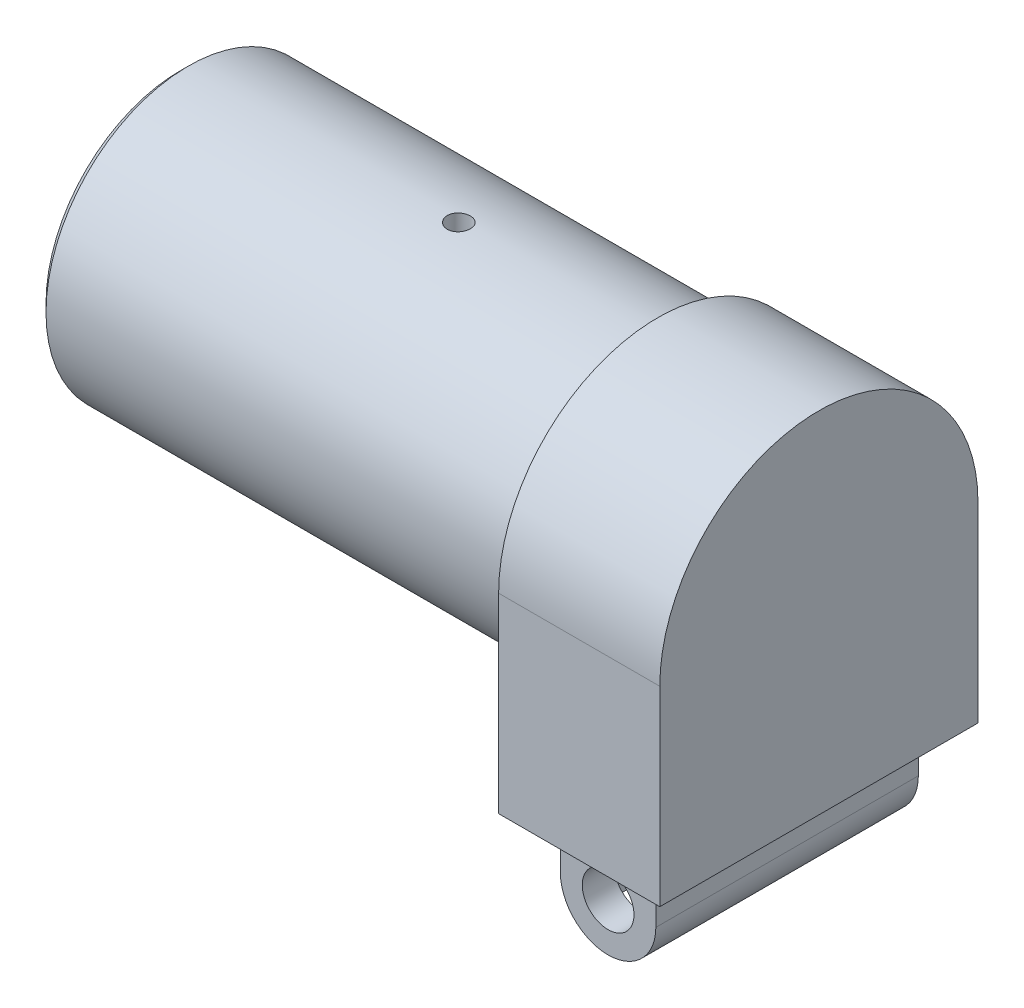
SolidWorks part; units mm, degrees
ref_plane "정면" through (0, 0, 0) normal (0, 0, 1) x (1, 0, 0)
ref_plane "윗면" through (0, 0, 0) normal (0, 1, 0) x (1, 0, 0)
ref_plane "우측면" through (0, 0, 0) normal (1, 0, 0) x (0, 0, -1)
sketch "스케치1" plane through (0, 0, 0) normal (1, 0, 0) x (0, 0, -1)
  line L0 (-20, 0) -> (-20, -24)
  line L1 (-20, -24) -> (20, -24)
  line L2 (20, -24) -> (20, 0)
  circle A0 centre (0, 0) radius 20
  dimension "D1" = 40
  dimension "D2" = 24
extrude "보스-돌출1" add sketch "스케치1" along normal blind 10 and the other way blind 10.26 contours A0 L0 L1 | A0 L1 L2 | A0
sketch "스케치4" plane through (-10.26, 0, 0) normal (-1, 0, 0) x (0, 0, 1)
  circle A0 centre (0, 0) radius 17.9
  dimension "D1" = 35.8
extrude "보스-돌출3" add sketch "스케치4" along normal blind 60
sketch "스케치15" plane through (0, 0, 0) normal (0, 0, 1) x (1, 0, 0)
  line L0 (-6, -30) -> (-6, -24)
  line L1 (-6, -24) -> (6, -24)
  line L2 (6, -24) -> (6, -30)
  line L3 (-10.26, -24) -> (10, -24) construction
  circle A0 centre (0, -30) radius 6
  point P9 (0, 0)
  dimension "D2" = 12
  dimension "D1" = 30
extrude "보스-돌출7" add sketch "스케치15" along normal blind 16.5 and the other way blind 16.5 contours A0 L1 L0 | A0 | A0 L2 L1
sketch "스케치17" plane through (0, 0, -16.5) normal (0, 0, -1) x (-1, 0, 0)
  circle A0 centre (0, -30) radius 3.25
  dimension "D1" = 6.5
extrude "컷-돌출3" cut sketch "스케치17" against normal blind 13
mirror "대칭 복사7" about plane through (0, 0, 0) normal (0, 0, 1) of "컷-돌출3"
ref_plane "평면2" through (0, 0, -10.5) normal (0, 0, -1) x (-1, 0, 0)
sketch "스케치18" plane through (0, 0, -10.5) normal (0, 0, -1) x (-1, 0, 0)
  line L0 (-4.2, -32.4249) -> (-4.2, -36)
  line L1 (0, -34.8497) -> (4.2, -32.4249)
  line L2 (4.2, -32.4249) -> (4.2, -27.5751)
  line L3 (4.2, -27.5751) -> (0, -25.1503)
  line L4 (0, -25.1503) -> (-4.2, -27.5751)
  line L5 (-4.2, -27.5751) -> (-4.2, -32.4249)
  line L6 (-4.2, -32.4249) -> (0, -34.8497)
  line L7 (-4.2, -36) -> (4.2, -36)
  line L8 (4.2, -36) -> (4.2, -32.4249)
  circle A0 centre (0, -30) radius 4.2 construction
  arc A1 (-6, -30) -> (6, -30) centre (0, -30) ccw construction
  dimension "D1" = 8.4
extrude "컷-돌출4" cut sketch "스케치18" against normal blind 1.95 and the other way blind 1.95 contours L7 L8 L1 L6 L0 | L5 L6 L1 L2 L3 L4
mirror "대칭 복사8" about plane through (0, 0, 0) normal (0, 0, 1) of "컷-돌출4"
fillet "필렛1" radius 3 2 edges at (-6, -24, 0) (6, -24, 0)
ref_plane "평면3" through (0, 17.9, 0) normal (0, 1, 0) x (1, 0, 0)
hole_wizard "M2.5 여유 구멍1" positions "스케치20" profile "스케치21" hole size "M2.5" standard "ISO" end condition through all
sketch "스케치20" plane through (0, 17.9, 0) normal (0, 1, 0) x (1, 0, 0)
  line L0 (-10.26, 17.9) -> (-10.26, -17.9) construction
  point P0 (-35.26, 0)
  point P6 (0, 0)
  dimension "D1" = 25
sketch "스케치21" plane through (-35.26, 17.9, 0) normal (1, 0, 0) x (0, 0, 1)
  line L0 (0, 0) -> (0, 53.9)
  line L1 (0, 53.9) -> (1.45, 53.9)
  line L2 (1.45, 53.9) -> (1.45, 0)
  line L5 (1.45, 0) -> (0, 0)
  line L11 (0, -6.35) -> (0, 107.95) construction
  dimension "관통 구멍 지름" = 2.9
  dimension "관통 구멍 깊이" = 53.9
chamfer "모따기1" distance 1 angle 45 1 edges at (-70.26, 0, 17.9)
